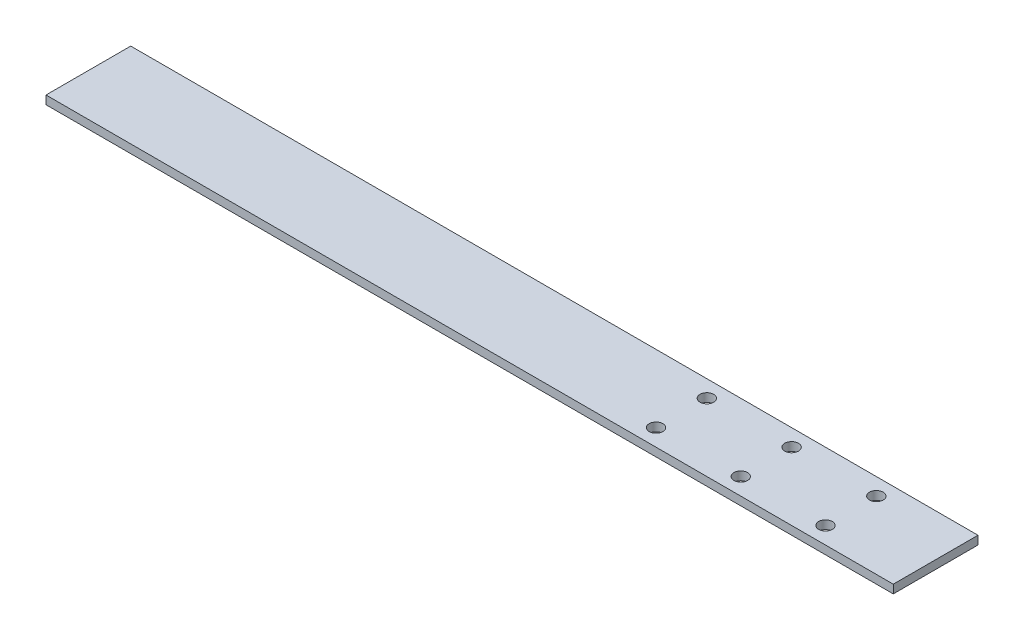
SolidWorks part; units mm, degrees
material "Copper"
ref_plane "Front Plane" through (0, 0, 0) normal (0, 0, 1) x (1, 0, 0)
ref_plane "Top Plane" through (0, 0, 0) normal (0, 1, 0) x (1, 0, 0)
ref_plane "Right Plane" through (0, 0, 0) normal (1, 0, 0) x (0, 0, -1)
sketch "Sketch1" plane through (0, 0, 0) normal (0, 1, 0) x (1, 0, 0)
  line L1 (0, 0) -> (500, 0)
  line L2 (0, 0) -> (0, 50)
  line L3 (0, 50) -> (500, 50)
  line L4 (500, 0) -> (500, 50)
  dimension "D1" = 500
  dimension "D2" = 50
extrude "Boss-Extrude1" add sketch "Sketch1" along normal blind 5
sketch "Sketch2" plane through (0, 5, 0) normal (0, 1, 0) x (1, 0, 0)
  line L0 (500, 25) -> (450, 25)
  line L1 (500, 0) -> (500, 50) construction
  line L2 (450, 25) -> (450, 50)
  line L3 (500, 50) -> (0, 50) construction
  line L4 (450, 50) -> (450, 0)
  line L5 (0, 0) -> (500, 0) construction
  circle A0 centre (450, 10) radius 4.05
  circle A1 centre (450, 40) radius 4.05
  circle A2 centre (400, 40) radius 4.05
  circle A3 centre (400, 10) radius 4.05
  circle A4 centre (350, 40) radius 4.05
  circle A5 centre (350, 10) radius 4.05
  dimension "D4" = 8.1
  dimension "D5" = 8.1
  dimension "D1" = 50
  dimension "D2" = 10
  dimension "D3" = 10
  dimension "D6" = 3
extrude "Cut-Extrude1" cut sketch "Sketch2" against normal blind 32 contours A0 | A1 | A2 | A3 | A4 | A5
